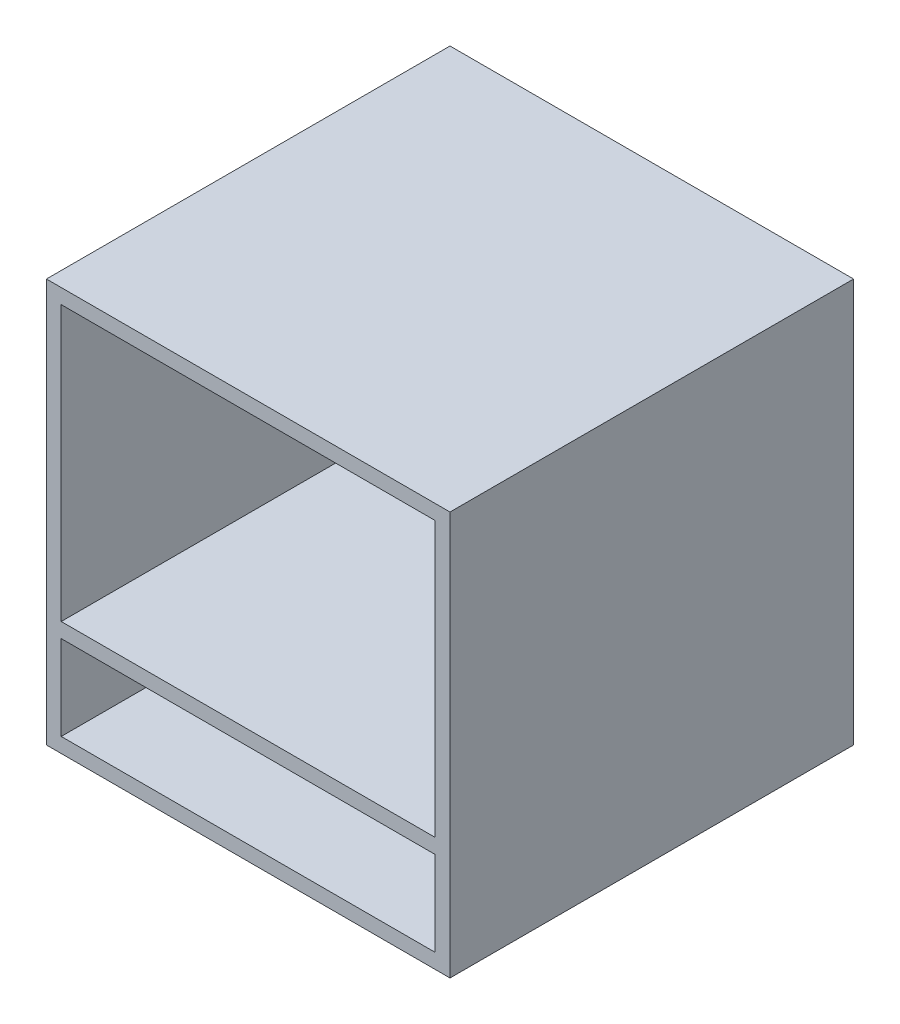
SolidWorks part; units mm, degrees
ref_plane "前视基准面" through (0, 0, 0) normal (0, 0, 1) x (1, 0, 0)
ref_plane "上视基准面" through (0, 0, 0) normal (0, 1, 0) x (1, 0, 0)
ref_plane "右视基准面" through (0, 0, 0) normal (1, 0, 0) x (0, 0, -1)
sketch "草图1" plane through (0, 0, 0) normal (0, 1, 0) x (1, 0, 0)
  line L1 (-150, 150) -> (150, 150)
  line L2 (-150, 150) -> (-150, -150)
  line L3 (-150, -150) -> (150, -150)
  line L4 (150, 150) -> (150, -150)
  line L5 (-150, 150) -> (150, -150) construction
  line L6 (-150, -150) -> (150, 150) construction
  point P0 (0, 0)
  dimension "D1" = 300
  dimension "D2" = 300
extrude "凸台-拉伸1" add sketch "草图1" along normal blind 300
shell "抽壳1" thickness 11
sketch "草图3" plane through (0, 0, 150) normal (0, 0, 1) x (1, 0, 0)
  line L0 (150, 300) -> (150, 0) construction
  line L1 (-150, 85) -> (150, 85)
  line L2 (-150, 85) -> (-150, 74)
  line L3 (-150, 74) -> (150, 74)
  line L4 (150, 85) -> (150, 74)
  line L5 (-150, 85) -> (150, 74) construction
  line L6 (-150, 74) -> (150, 85) construction
  line L7 (-150, 300) -> (150, 300) construction
  line L8 (-150, 300) -> (-150, 0) construction
  point P0 (0, 79.5)
  dimension "D1" = 215
  dimension "D2" = 11
extrude "凸台-拉伸2" add sketch "草图3" against normal blind 300
